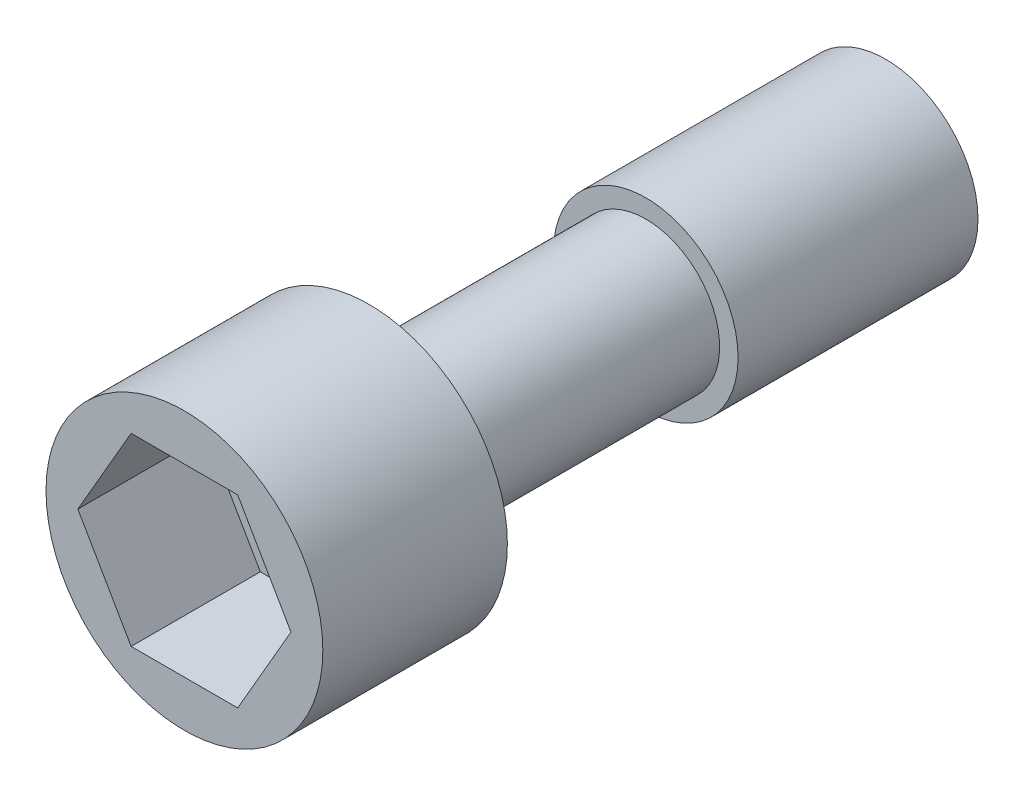
SolidWorks part; units mm, degrees
ref_plane "Front Plane" through (0, 0, 0) normal (0, 0, 1) x (1, 0, 0)
ref_plane "Top Plane" through (0, 0, 0) normal (0, 1, 0) x (1, 0, 0)
ref_plane "Right Plane" through (0, 0, 0) normal (1, 0, 0) x (0, 0, -1)
sketch "Sketch1" plane through (0, 0, 0) normal (0, 0, 1) x (1, 0, 0)
  circle A0 centre (0, 0) radius 7.5
  dimension "D1" = 15
extrude "Boss-Extrude1" add sketch "Sketch1" along normal blind 10
sketch "Sketch2" plane through (0, 0, 0) normal (0, 0, -1) x (-1, 0, 0)
  circle A0 centre (0, 0) radius 4
  dimension "D1" = 8
extrude "Boss-Extrude2" add sketch "Sketch2" along normal blind 15
sketch "Sketch3" plane through (0, 0, -15) normal (0, 0, -1) x (-1, 0, 0)
  circle A0 centre (0, 0) radius 5
  dimension "D1" = 10
extrude "Boss-Extrude3" add sketch "Sketch3" along normal blind 13
sketch "Sketch4" plane through (0, 0, 10) normal (0, 0, 1) x (1, 0, 0)
  line L1 (5.7735, 0) -> (2.8868, 5)
  line L2 (2.8868, 5) -> (-2.8868, 5)
  line L3 (-2.8868, 5) -> (-5.7735, 0)
  line L4 (-5.7735, 0) -> (-2.8868, -5)
  line L5 (-2.8868, -5) -> (2.8868, -5)
  line L6 (2.8868, -5) -> (5.7735, 0)
  circle A0 centre (0, 0) radius 5 construction
  dimension "D1" = 10
extrude "Cut-Extrude1" cut sketch "Sketch4" against normal blind 7 and the other way through all
